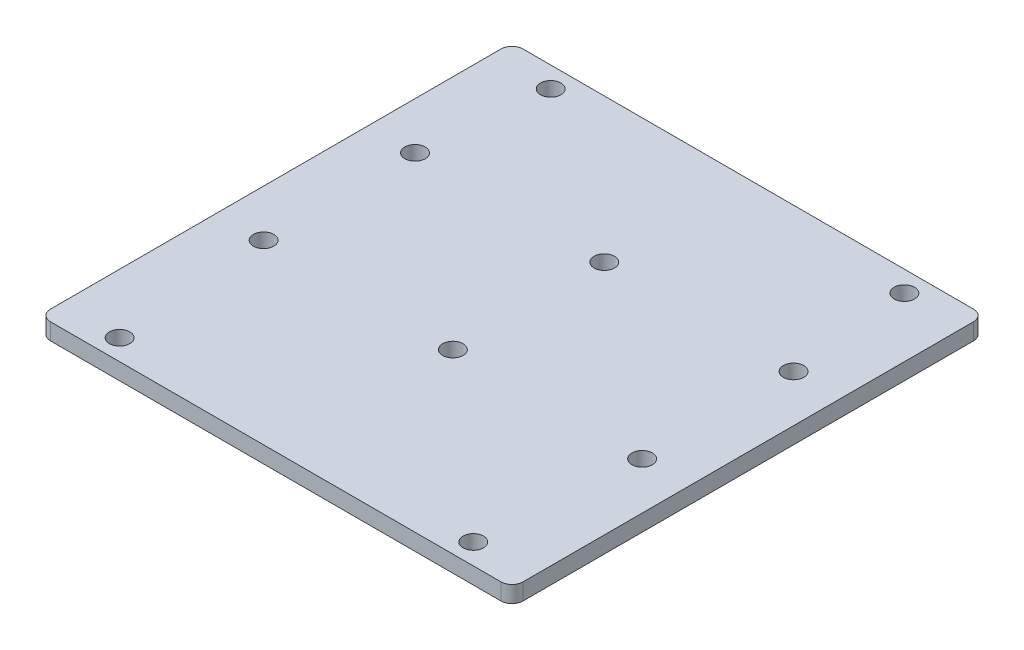
SolidWorks part; units mm, degrees
material "Acrylic (Medium-high impact)"
ref_plane "Front Plane" through (0, 0, 0) normal (0, 0, 1) x (1, 0, 0)
ref_plane "Top Plane" through (0, 0, 0) normal (0, 1, 0) x (1, 0, 0)
ref_plane "Right Plane" through (0, 0, 0) normal (1, 0, 0) x (0, 0, -1)
sketch "Sketch1" plane through (0, 0, 0) normal (0, 1, 0) x (1, 0, 0)
  line L1 (42.75, -42.75) -> (-42.75, -42.75)
  line L2 (42.75, -42.75) -> (42.75, 42.75)
  line L3 (42.75, 42.75) -> (-42.75, 42.75)
  line L4 (-42.75, -42.75) -> (-42.75, 42.75)
  line L5 (42.75, -42.75) -> (-42.75, 42.75) construction
  line L6 (42.75, 42.75) -> (-42.75, -42.75) construction
  point P0 (0, 0)
  dimension "D1" = 85.5
  dimension "D2" = 85.5
extrude "Boss-Extrude1" add sketch "Sketch1" along normal blind 3
fillet "Fillet1" radius 2 4 edges at (-42.75, 1.5, -42.75) (42.75, 1.5, -42.75) (-42.75, 1.5, 42.75) (42.75, 1.5, 42.75)
sketch "Sketch2" plane through (0, 0, 0) normal (0, -1, 0) x (1, 0, 0)
  circle A4 centre (-32, -39) radius 1.85
  circle A5 centre (32, -39) radius 1.85
  circle A6 centre (-32, 39) radius 1.85
  circle A7 centre (32, 39) radius 1.85
  dimension "D1" = 3.7
  dimension "D2" = 3.7
  dimension "D3" = 3.7
  dimension "D4" = 3.7
extrude "Cut-Extrude1" cut sketch "Sketch2" against normal blind 10
sketch "Sketch3" plane through (0, 0, 0) normal (0, -1, 0) x (1, 0, 0)
  circle A6 centre (-34.25, -16.7) radius 1.85
  circle A7 centre (0, -16.7) radius 1.85
  circle A8 centre (34.25, -16.7) radius 1.85
  circle A9 centre (0, 10.7) radius 1.85
  circle A10 centre (-34.25, 10.7) radius 1.85
  circle A11 centre (34.25, 10.7) radius 1.85
  dimension "D1" = 3.7
extrude "Cut-Extrude2" cut sketch "Sketch3" against normal blind 5
